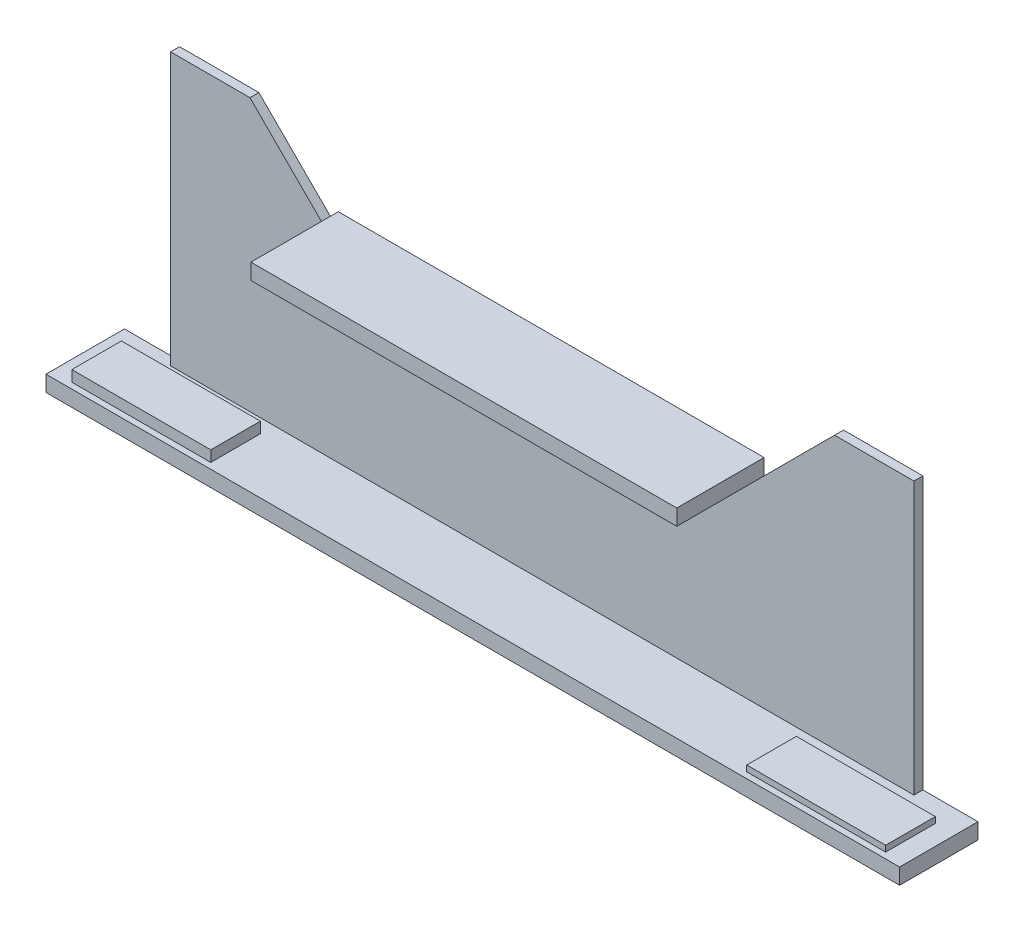
SolidWorks part; units mm, degrees
ref_plane "前视基准面" through (0, 0, 0) normal (0, 0, 1) x (1, 0, 0)
ref_plane "上视基准面" through (0, 0, 0) normal (0, 1, 0) x (1, 0, 0)
ref_plane "右视基准面" through (0, 0, 0) normal (1, 0, 0) x (0, 0, -1)
sketch "草图1" plane through (0, 0, 0) normal (0, 0, 1) x (1, 0, 0)
  line L0 (-1000, 0) -> (49000, 0) construction
  line L1 (0, -1000) -> (0, 49000) construction
  line L2 (0, 0) -> (860, 0)
  line L3 (55.5, -562.2618) -> (55.5, 49437.7382) construction
  line L4 (-1038.7035, 16) -> (48961.2965, 16) construction
  line L5 (860, -1000) -> (860, 49000) construction
  line L6 (804.5, -950.8793) -> (804.5, 49049.1207) construction
  line L7 (-663.1285, 290) -> (49336.8715, 290) construction
  line L8 (-660.6051, 210) -> (49339.3949, 210) construction
  line L9 (0, 0) -> (0, 16)
  line L10 (0, 16) -> (55.5, 16)
  line L11 (860, 0) -> (860, 16)
  line L12 (860, 16) -> (804.5, 16)
  line L13 (55.5, 290) -> (135.5, 290)
  line L14 (804.5, 290) -> (724.5, 290)
  line L15 (55.5, 16) -> (55.5, 290)
  line L16 (804.5, 16) -> (804.5, 290)
  line L17 (135.5, 290) -> (215.5, 210) construction
  line L18 (724.5, 290) -> (644.5, 210) construction
  line L19 (135.5, 290) -> (215.5, 210)
  line L20 (724.5, 290) -> (644.5, 210)
  line L21 (215.5, 210) -> (215.5, 226)
  line L22 (95.5, -794.5532) -> (95.5, 49205.4468) construction
  line L23 (764.5, -804.9005) -> (764.5, 49195.0995) construction
  line L24 (-871.0333, 90) -> (49128.9667, 90) construction
  line L25 (-452.5392, 170) -> (49547.4608, 170) construction
  line L26 (-439.8924, 250) -> (49560.1076, 250) construction
  line L27 (644.5, 210) -> (644.5, 226)
  line L28 (215.5, 226) -> (644.5, 226)
  point P10 (0, 16)
  point P15 (860, 16)
  point P17 (804.5, 16)
  point P18 (55.5, 16)
  point P22 (55.5, 290)
  point P28 (804.5, 290)
  point P44 (764.5, 90)
  point P46 (764.5, 170)
  point P47 (764.5, 250)
  point P48 (95.5, 90)
  point P49 (95.5, 170)
  point P50 (95.5, 250)
  dimension "D1" = 860
  dimension "D2" = 55.5
  dimension "D3" = 16
  dimension "D4" = 860
  dimension "D5" = 55.5
  dimension "D6" = 290
  dimension "D7" = 210
  dimension "D8" = 80
  dimension "D9" = 80
  dimension "D10" = 45
  dimension "D11" = 45
  dimension "D12" = 40
  dimension "D13" = 40
  dimension "D14" = 90
  dimension "D15" = 80
  dimension "D16" = 80
  dimension "D23" = 16
  dimension "D24" = 16
extrude "凸台-拉伸2" add sketch "草图1" along normal blind 9
sketch "草图3" plane through (0, 0, 9) normal (0, 0, 1) x (1, 0, 0)
  line L0 (0, 0) -> (860, 0)
  line L1 (0, 0) -> (0, 16)
  line L2 (0, 16) -> (860, 16)
  line L3 (860, 16) -> (860, 0)
extrude "凸台-拉伸3" add sketch "草图3" along normal blind 70
sketch "草图4" plane through (0, 16, 0) normal (0, 1, 0) x (1, 0, 0)
  line L0 (-1008.5696, -48) -> (48991.4304, -48) construction
  line L1 (55.5, 0) -> (0, 0) construction
  line L3 (20, -1060.4184) -> (20, 48939.5816) construction
  line L4 (0, -79) -> (0, 0) construction
  line L5 (-980, -23) -> (49020, -23) construction
  line L7 (20, -23) -> (160, -23)
  line L8 (20, -23) -> (20, -73)
  line L9 (20, -73) -> (160, -73)
  line L10 (160, -23) -> (160, -73)
  point P9 (20, -23)
  dimension "D1" = 48
  dimension "D2" = 20
  dimension "D3" = 25
  dimension "D4" = 140
  dimension "D5" = 50
extrude "凸台-拉伸5" add sketch "草图4" along normal blind 11
sketch "草图6" plane through (0, 16, 0) normal (0, 1, 0) x (1, 0, 0)
  line L0 (840, -1040.034) -> (840, 48959.966) construction
  line L1 (860, -79) -> (860, 0) construction
  line L2 (-442.9077, -23) -> (49557.0923, -23) construction
  line L3 (860, 0) -> (804.5, 0) construction
  line L5 (840, -23) -> (700, -23)
  line L6 (840, -23) -> (840, -73)
  line L7 (840, -73) -> (700, -73)
  line L8 (700, -23) -> (700, -73)
  point P8 (840, -23)
  dimension "D1" = 20
  dimension "D2" = 23
  dimension "D3" = 140
  dimension "D4" = 50
extrude "凸台-拉伸6" add sketch "草图6" along normal blind 6
sketch "草图10" plane through (0, 0, 9) normal (0, 0, 1) x (1, 0, 0)
  line L1 (215.5, 226) -> (644.5, 226)
  line L2 (215.5, 226) -> (215.5, 210)
  line L3 (215.5, 210) -> (644.5, 210)
  line L4 (644.5, 226) -> (644.5, 210)
  dimension "D1" = 429
  dimension "D2" = 16
extrude "凸台-拉伸8" add sketch "草图10" along normal blind 79
